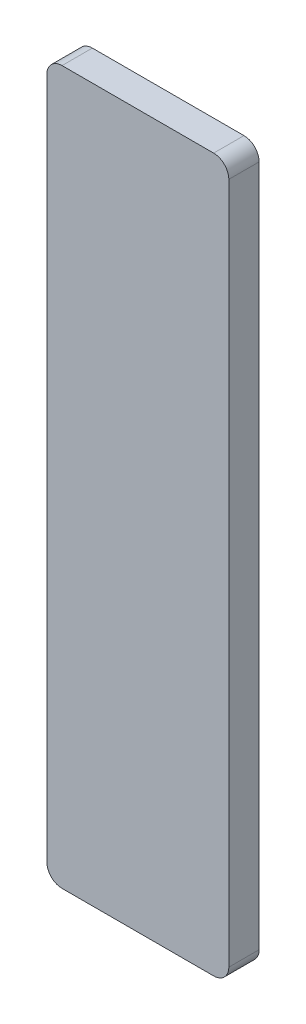
SolidWorks part; units mm, degrees
ref_plane "Front Plane" through (0, 0, 0) normal (0, 0, 1) x (1, 0, 0)
ref_plane "Top Plane" through (0, 0, 0) normal (0, 1, 0) x (1, 0, 0)
ref_plane "Right Plane" through (0, 0, 0) normal (1, 0, 0) x (0, 0, -1)
sketch "Sketch1" plane through (0, 0, 0) normal (0, 0, 1) x (1, 0, 0)
  line L1 (-50, -235) -> (50, -235)
  line L2 (-60, -225) -> (-60, 225)
  line L3 (-50, 235) -> (50, 235)
  line L4 (60, -225) -> (60, 225)
  line L5 (-60, -235) -> (60, 235) construction
  line L6 (-60, 235) -> (60, -235) construction
  arc A0 (-50, -235) -> (-60, -225) centre (-50, -225) cw
  arc A1 (50, -235) -> (60, -225) centre (50, -225) ccw
  arc A2 (50, 235) -> (60, 225) centre (50, 225) cw
  arc A3 (-50, 235) -> (-60, 225) centre (-50, 225) ccw
  point P0 (0, 0)
  dimension "D1" = 10
  dimension "D2" = 10
  dimension "D3" = 100
  dimension "D4" = 450
extrude "Boss-Extrude1" add sketch "Sketch1" along normal blind 20
